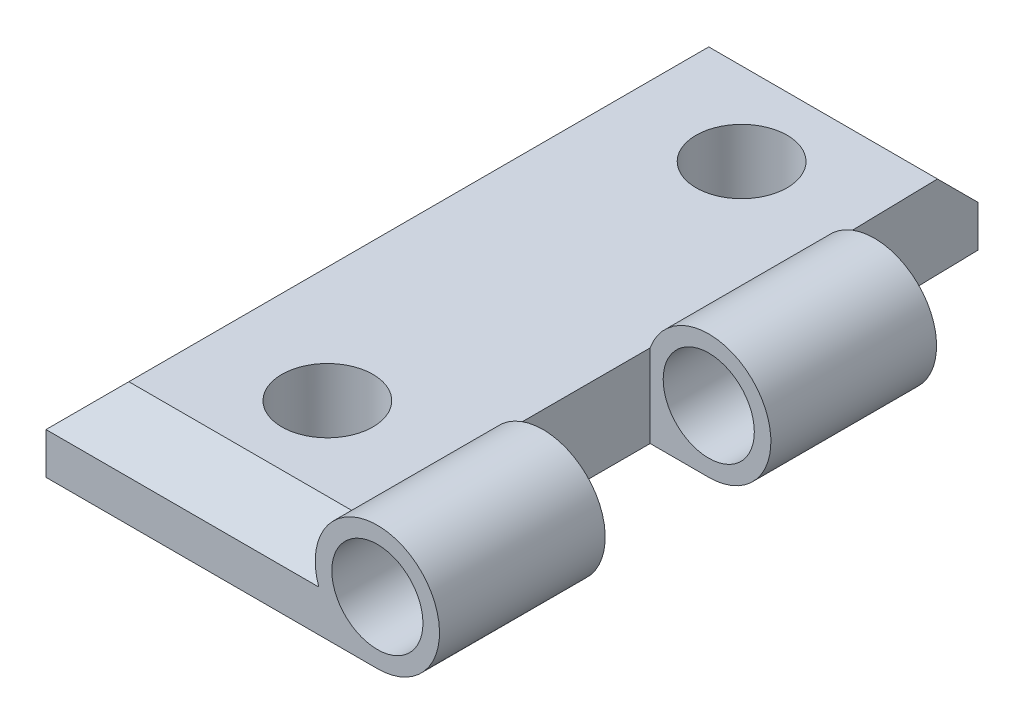
SolidWorks part; units mm, degrees
ref_plane "Ön Düzlem" through (0, 0, 0) normal (0, 0, 1) x (1, 0, 0)
ref_plane "Üst Düzlem" through (0, 0, 0) normal (0, 1, 0) x (1, 0, 0)
ref_plane "Sağ Düzlem" through (0, 0, 0) normal (1, 0, 0) x (0, 0, -1)
sketch "Çizim1" plane through (0, 0, 0) normal (0, 0, 1) x (1, 0, 0)
  line L0 (-64.2339, 5) -> (-64.2339, 0)
  line L1 (-64.2339, 0) -> (-44.2339, 0)
  line L2 (-64.2339, 5) -> (-47.7694, 5)
  arc A1 (-44.2339, 0) -> (-47.7694, 5) centre (-44.2339, 3.75) ccw
  circle A2 centre (-44.2339, 3.75) radius 2.75
  dimension "D2" = 5.5
  dimension "D3" = 7.5
  dimension "D1" = 5
  dimension "D4" = 20
extrude "Yükseklik-Ekstrüzyon1" add sketch "Çizim1" along normal blind 40
chamfer "Pah3" distance 2.5 3 edges at (-56.0016, 5, 0) (-64.2339, 5, 20) (-56.0016, 5, 40)
sketch "Çizim2" plane through (0, 0, 0) normal (0, 1, 0) x (1, 0, 0)
  line L0 (-54.7516, -2.5) -> (-54.7516, -37.5) construction
  line L1 (-47.7694, -2.5) -> (-61.7339, -2.5) construction
  line L2 (-61.7339, -37.5) -> (-47.7694, -37.5) construction
  line L4 (-64.2339, 0) -> (-47.7694, 0) construction
  line L5 (-40.4839, -30) -> (-47.7694, -30)
  line L6 (-40.4839, -40) -> (-40.4839, 0) construction
  line L7 (-47.7694, -37.5) -> (-47.7694, -2.5) construction
  line L8 (-47.7694, -30) -> (-47.7694, -20)
  line L9 (-47.7694, -20) -> (-40.4839, -20)
  line L10 (-40.4839, -20) -> (-40.4839, -30)
  line L11 (-40.4839, 0) -> (-47.9839, 0)
  line L12 (-47.9839, 0) -> (-47.7694, -10)
  line L13 (-47.7694, -10) -> (-40.4839, -10)
  line L14 (-40.4839, -10) -> (-40.4839, 0)
  line L15 (-47.9839, -40) -> (-40.4839, -40) construction
  circle A0 centre (-54.7516, -32.5) radius 2.75
  circle A1 centre (-54.7516, -7.5) radius 2.75
  dimension "D1" = 5.5
  dimension "D2" = 5.5
  dimension "D3" = 7.5
  dimension "D5" = 10
  dimension "D4" = 25
  dimension "D6" = 10
  dimension "D7" = 10
extrude "Kes-Ekstrüzyon1" cut sketch "Çizim2" along normal blind 40
sketch "Çizim3" plane through (0, 0, 0) normal (1, 0, 0) x (0, 0, -1)
  line L0 (-0.8753, 3.3753) -> (-1.7844, 4.2844)
  line L1 (-1.7844, 4.2844) -> (0.5917, 4.2844)
  line L2 (0.5917, 4.2844) -> (0.3689, 3.1635)
  line L3 (0.3689, 3.1635) -> (-0.8753, 3.3753)
extrude "Kes-Ekstrüzyon2" cut sketch "Çizim3" against normal blind 88
